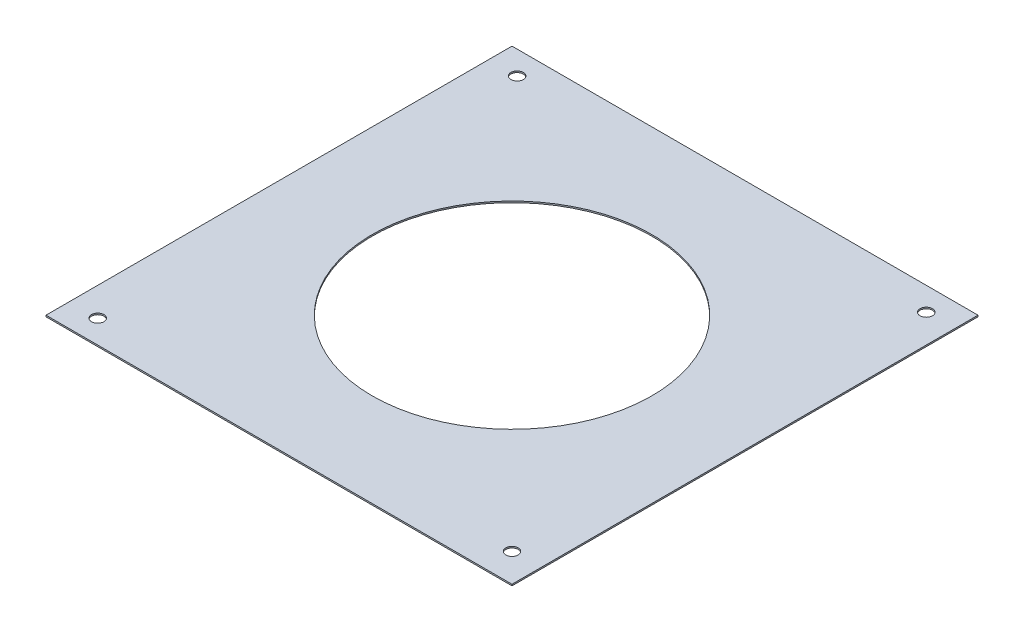
SolidWorks part; units mm, degrees
ref_plane "Front Plane" through (0, 0, 0) normal (0, 0, 1) x (1, 0, 0)
ref_plane "Top Plane" through (0, 0, 0) normal (0, 1, 0) x (1, 0, 0)
ref_plane "Right Plane" through (0, 0, 0) normal (1, 0, 0) x (0, 0, -1)
sketch "Sketch1" plane through (0, 0, 0) normal (0, 1, 0) x (1, 0, 0)
  line L1 (-127, -127) -> (127, -127)
  line L2 (-127, -127) -> (-127, 127)
  line L3 (-127, 127) -> (127, 127)
  line L4 (127, -127) -> (127, 127)
  line L5 (-127, -127) -> (127, 127) construction
  line L6 (-127, 127) -> (127, -127) construction
  line L7 (-111.506, -114.3) -> (111.506, -114.3) construction
  line L8 (-111.506, -114.3) -> (-111.506, 114.3) construction
  line L9 (-111.506, 114.3) -> (111.506, 114.3) construction
  line L10 (111.506, -114.3) -> (111.506, 114.3) construction
  line L11 (-111.506, -114.3) -> (111.506, 114.3) construction
  line L12 (-111.506, 114.3) -> (111.506, -114.3) construction
  circle A0 centre (-111.506, 114.3) radius 3.3782
  circle A1 centre (111.506, 114.3) radius 3.3782
  circle A2 centre (111.506, -111.506) radius 3.3782
  circle A3 centre (-111.506, -114.3) radius 3.3782
  point P0 (0, 0)
  point P6 (0, 0)
  dimension "D4" = 6.7564
  dimension "D1" = 254
  dimension "D2" = 228.6
  dimension "D3" = 223.012
extrude "Boss-Extrude1" add sketch "Sketch1" along normal blind 0.7937
sketch "Sketch3" plane through (0, 0.7937, 0) normal (0, 1, 0) x (1, 0, 0)
  circle A0 centre (0, 0) radius 76.2
  dimension "D1" = 152.4
extrude "Cut-Extrude1" cut sketch "Sketch3" against normal through all
